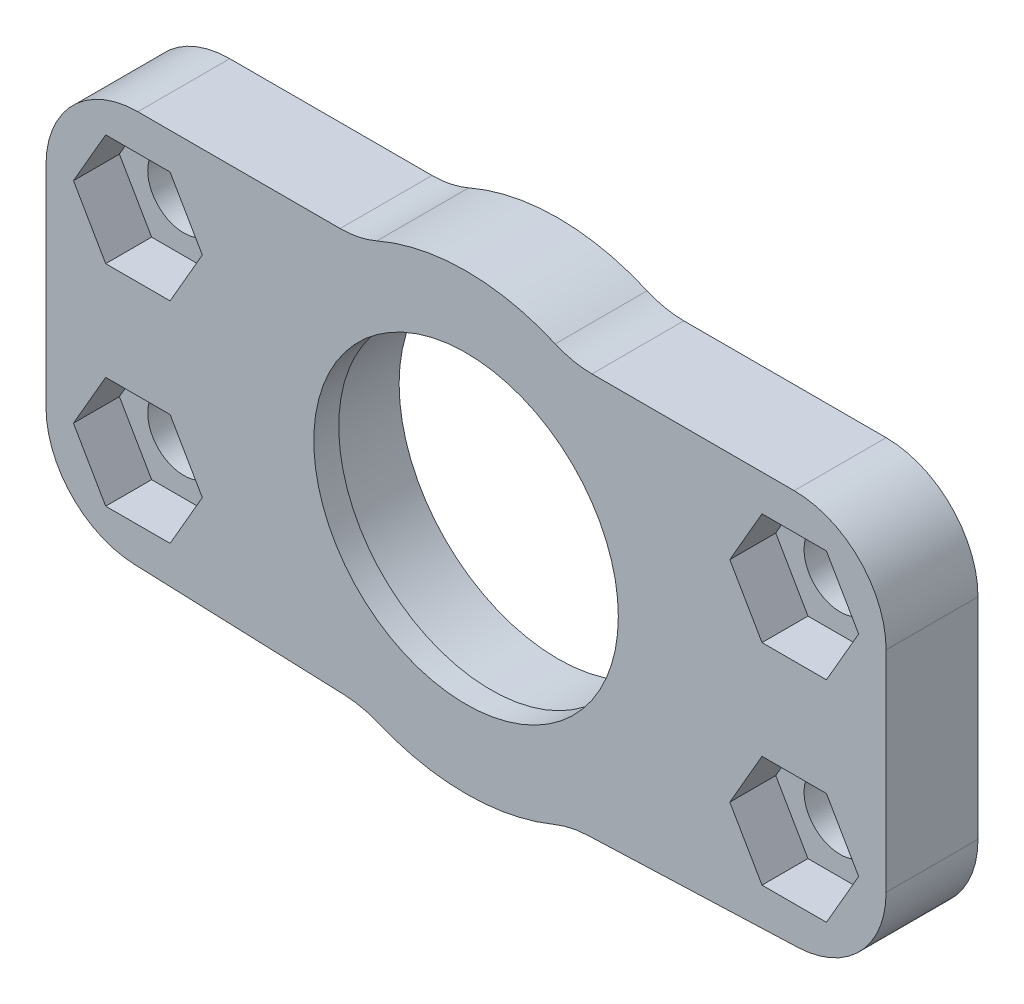
SolidWorks part; units mm, degrees
ref_plane "Спереди" through (0, 0, 0) normal (0, 0, 1) x (1, 0, 0)
ref_plane "Сверху" through (0, 0, 0) normal (0, 1, 0) x (1, 0, 0)
ref_plane "Справа" through (0, 0, 0) normal (1, 0, 0) x (0, 0, -1)
sketch "Эскиз1" plane through (0, 0, 0) normal (0, 0, 1) x (1, 0, 0)
  line L0 (-32, 0) -> (32, 0) construction
  line L1 (-9.2823, -15.6024) -> (-25.2658, -14.995)
  line L2 (-32, 15) -> (-8, 15)
  line L3 (0, 17) -> (0, -17.5) construction
  line L4 (8, 15) -> (32, 15)
  line L5 (-32, -8) -> (-32, 15)
  line L6 (32, 15) -> (32, -8)
  line L7 (-9.5671, -23.097) -> (0, 0) construction
  line L8 (9.2823, -15.6024) -> (25.2658, -14.995)
  line L10 (0, 0) -> (9.5671, -23.097) construction
  circle A0 centre (0, 0) radius 12 construction
  circle A1 centre (0, 0) radius 12.1
  arc A2 (-32, -8) -> (-25.2658, -14.995) centre (-25, -8) ccw
  arc A3 (-9.5671, -23.097) -> (9.5671, -23.097) centre (0, 0) ccw construction
  circle A4 centre (-9.5671, -23.097) radius 7 construction
  arc A5 (-8, 15) -> (8, 15) centre (0, 0) cw
  arc A6 (6.697, -16.1679) -> (-6.697, -16.1679) centre (0, 0) cw
  circle A7 centre (9.5671, -23.097) radius 7 construction
  arc A8 (-6.697, -16.1679) -> (-9.2823, -15.6024) centre (-9.5671, -23.097) ccw
  arc A9 (6.697, -16.1679) -> (9.2823, -15.6024) centre (9.5671, -23.097) cw
  arc A10 (32, -8) -> (25.2658, -14.995) centre (25, -8) cw
  arc A15 (8, 15) -> (-8, 15) centre (0, 0) ccw construction
  dimension "D1" = 24
  dimension "D4" = 5
  dimension "D7" = 30
  dimension "D2" = 0.5
  dimension "D8" = 45
  dimension "D6" = 25
  dimension "D5" = 7
  dimension "D10" = 14
  dimension "D9" = 25
  dimension "D3" = 8
extrude "Бобышка-Вытянуть1" add sketch "Эскиз1" along normal blind 7
ref_plane "Плоскость1" through (0, 0, 5) normal (0, 0, -1) x (-1, 0, 0)
fillet "Скругление3" radius 7 4 edges at (8, 15, 3.5) (-8, 15, 3.5) (-32, 15, 3.5) (32, 15, 3.5)
hole_wizard "Цековка для винта с внутренним шестигранником M51" [suppressed] positions "Эскиз6" profile "Эскиз5" counterbore size "M5" standard "Ansi Metric"
sketch "Эскиз6" plane through (0, 0, 7) normal (0, 0, 1) x (1, 0, 0)
  line L0 (0, 0) -> (-32, 0) construction
  line L1 (-32, 8) -> (-32, -20) construction
  arc A0 (32, 8) -> (25, 15) centre (25, 8) ccw construction
  arc A1 (-25, 15) -> (-32, 8) centre (-25, 8) ccw construction
  point P2 (-25, 8)
  point P29 (25, 8)
  point P59 (25, -8)
  point P60 (-25, -8)
sketch "Эскиз5" plane through (-25, 8, 7) normal (1, 0, 0) x (0, -1, 0)
  line L0 (0, 0) -> (0, 7)
  line L1 (0, 7) -> (2.75, 7)
  line L3 (2.75, 7) -> (2.75, 3.5)
  line L4 (2.75, 3.5) -> (5.1, 3.5)
  line L5 (5.1, 3.5) -> (5.1, 0)
  line L7 (5.1, 0) -> (0, 0)
  line L11 (0, -6.35) -> (0, 107.95) construction
  dimension "Диаметр сквозного отверстия" = 5.5
  dimension "Глубина сквозного отверстия" = 7
  dimension "Диаметр цековки" = 10.2
  dimension "Глубина цековки" = 3.5
hole_wizard "Отверстие с зазором M52" [suppressed] positions "Эскиз12" profile "Эскиз11" hole size "M5" standard "Ansi Metric"
sketch "Эскиз12" plane through (0, 0, 7) normal (0, 0, 1) x (1, 0, 0)
  arc A0 (-32, -20) -> (-19.2137, -23.9393) centre (-25, -20) ccw construction
  arc A1 (19.2137, -23.9393) -> (32, -20) centre (25, -20) ccw construction
  point P0 (-25, -20)
  point P2 (25, -20)
sketch "Эскиз11" plane through (-25, -20, 7) normal (1, 0, 0) x (0, -1, 0)
  line L0 (0, 0) -> (0, 27.6524)
  line L1 (0, 27.6524) -> (2.75, 26)
  line L2 (2.75, 26) -> (2.75, 0)
  line L5 (2.75, 0) -> (0, 0)
  line L10 (0, 27.6524) -> (-2.75, 26) construction
  line L11 (0, -6.35) -> (0, 107.95) construction
  dimension "Диаметр отверстия" = 5.5
  dimension "Глубина отверстия" = 26
  dimension "Угол заточки сверла" = 118
sketch "Эскиз7" plane through (0, 0, 7) normal (0, 0, 1) x (1, 0, 0)
  circle A0 centre (0, 0) radius 12.1 construction
  circle A1 centre (0, 0) radius 12.1
  circle A2 centre (0, 0) radius 11.6
  dimension "D1" = 0.5
extrude "Бобышка-Вытянуть2" add sketch "Эскиз7" against normal offset from surface (1.9 mm away) 0.1 up to plane "Плоскость1"
hole_wizard "Отверстие с зазором M53" positions "Эскиз15" profile "Эскиз14" hole size "M5" standard "Ansi Metric" end condition through all
sketch "Эскиз15" plane through (0, 0, 7) normal (0, 0, 1) x (1, 0, 0)
  arc A0 (-25, 15) -> (-32, 8) centre (-25, 8) ccw construction
  arc A1 (32, 8) -> (25, 15) centre (25, 8) ccw construction
  point P0 (-25, 8)
  point P3 (25, 8)
sketch "Эскиз14" plane through (-25, 8, 7) normal (1, 0, 0) x (0, -1, 0)
  line L0 (0, 0) -> (0, 7)
  line L1 (0, 7) -> (2.75, 7)
  line L2 (2.75, 7) -> (2.75, 0)
  line L5 (2.75, 0) -> (0, 0)
  line L11 (0, -6.35) -> (0, 107.95) construction
  dimension "Диаметр сквозного отверстия" = 5.5
  dimension "Глубина сквозного отверстия" = 7
hole_wizard "Отверстие с зазором M54" positions "Эскиз17" profile "Эскиз16" hole size "M5" standard "Ansi Metric" end condition through all
sketch "Эскиз17" plane through (-20.8504, 7.1997, 7) normal (0, 0, -1) x (-1, 0, 0)
  arc A0 (-52.8504, -15.1997) -> (-46.1162, -22.1947) centre (-45.8504, -15.1997) ccw construction
  arc A1 (4.4155, -22.1947) -> (11.1496, -15.1997) centre (4.1496, -15.1997) ccw construction
  point P0 (-45.8504, -15.1997)
  point P2 (4.1496, -15.1997)
sketch "Эскиз16" plane through (25, -8, 7) normal (1, 0, 0) x (0, -1, 0)
  line L0 (0, 0) -> (0, 7)
  line L1 (0, 7) -> (2.75, 7)
  line L2 (2.75, 7) -> (2.75, 0)
  line L5 (2.75, 0) -> (0, 0)
  line L11 (0, -6.35) -> (0, 107.95) construction
  dimension "Диаметр сквозного отверстия" = 5.5
  dimension "Глубина сквозного отверстия" = 7
sketch "Эскиз18" plane through (0, 0, 7) normal (0, 0, -1) x (1, 0, 0)
  line L0 (25, -15) -> (9.5917, -15) construction
  line L1 (20.0925, -8) -> (22.5463, -12.25)
  line L2 (22.5463, -12.25) -> (27.4537, -12.25)
  line L3 (27.4537, -12.25) -> (29.9075, -8)
  line L4 (29.9075, -8) -> (27.4537, -3.75)
  line L5 (27.4537, -3.75) -> (22.5463, -3.75)
  line L6 (22.5463, -3.75) -> (20.0925, -8)
  line L7 (-27.4537, -3.75) -> (-29.9075, -8)
  line L8 (-29.9075, -8) -> (-27.4537, -12.25)
  line L9 (-27.4537, -12.25) -> (-22.5463, -12.25)
  line L10 (-22.5463, -12.25) -> (-20.0925, -8)
  line L11 (-20.0925, -8) -> (-22.5463, -3.75)
  line L12 (-22.5463, -3.75) -> (-27.4537, -3.75)
  line L13 (-32, 0) -> (32, 0) construction
  line L14 (-32, -8) -> (-32, 8) construction
  line L15 (32, 8) -> (32, -8) construction
  line L16 (20.0925, 8) -> (22.5463, 12.25)
  line L17 (22.5463, 12.25) -> (27.4537, 12.25)
  line L18 (27.4537, 12.25) -> (29.9075, 8)
  line L19 (29.9075, 8) -> (27.4537, 3.75)
  line L20 (27.4537, 3.75) -> (22.5463, 3.75)
  line L21 (22.5463, 3.75) -> (20.0925, 8)
  line L22 (-22.5463, 12.25) -> (-20.0925, 8)
  line L23 (-27.4537, 12.25) -> (-22.5463, 12.25)
  line L24 (-29.9075, 8) -> (-27.4537, 12.25)
  line L25 (-27.4537, 3.75) -> (-29.9075, 8)
  line L26 (-20.0925, 8) -> (-22.5463, 3.75)
  line L27 (-22.5463, 3.75) -> (-27.4537, 3.75)
  circle A0 centre (25, -8) radius 4.25 construction
  circle A1 centre (-25, -8) radius 4.25 construction
  dimension "D1" = 8.5
  dimension "D2" = 8.5
extrude "Вырез-Вытянуть1" cut sketch "Эскиз18" along normal blind 3.5
hole_wizard "Сверление под метчик M2x0.41" [suppressed] positions "Эскиз20" profile "Эскиз19" hole size "M2x0.4" standard "Ansi Metric"
sketch "Эскиз20" plane through (0, 8, 0) normal (0, 1, 0) x (1, 0, 0)
  line L0 (0, 0) -> (0, 17) construction
  arc A0 (6.7941, 15.5833) -> (-6.7941, 15.5833) centre (0, 0) ccw construction
  point P0 (-14.5, 0)
  point P2 (14.5, 0)
  dimension "D1" = 14.5
sketch "Эскиз19" plane through (-14.5, 8, 0) normal (1, 0, 0) x (0, 0, 1)
  line L0 (0, 0) -> (0, 8)
  line L1 (0, 8) -> (0.8, 8)
  line L2 (0.8, 8) -> (0.8, 0)
  line L5 (0.8, 0) -> (0, 0)
  line L11 (0, -6.35) -> (0, 107.95) construction
  dimension "Диаметр сквозного отверстия" = 1.6
  dimension "Глубина сквозного отверстия" = 8
sketch "Эскиз21" plane through (0, 0, 7) normal (0, 0, 1) x (1, 0, 0)
  circle A0 centre (0, 0) radius 13.25
  dimension "D1" = 26.5
extrude "Вырез-Вытянуть2" [suppressed] cut sketch "Эскиз21" against normal blind 0.5
sketch "Эскиз22" [suppressed] plane through (0, 0, 7) normal (0, 0, 1) x (1, 0, 0)
  circle A0 centre (25, -20) radius 2.75 construction
  circle A1 centre (25, -20) radius 2.75
  circle A2 centre (-25, -20) radius 2.75 construction
  circle A3 centre (-25, -20) radius 2.75
  circle A4 centre (-25, -20) radius 4.25
  circle A5 centre (25, -20) radius 4.25
  dimension "D1" = 1.5
  dimension "D2" = 1.5
extrude "Бобышка-Вытянуть3" [suppressed] add sketch "Эскиз22" along normal blind 0.5
